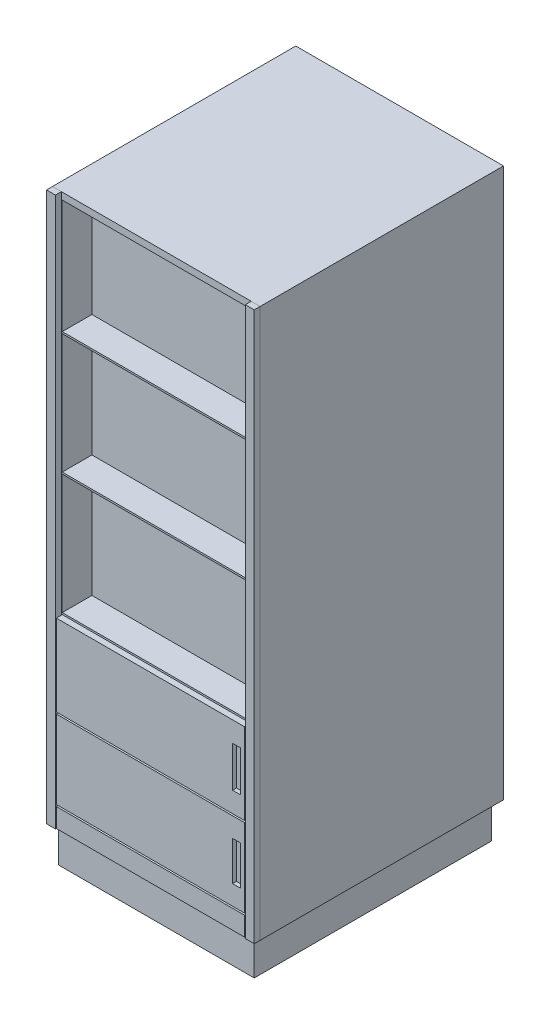
SolidWorks part; units mm, degrees
ref_plane "Front Plane" through (0, 0, 0) normal (0, 0, 1) x (1, 0, 0)
ref_plane "Top Plane" through (0, 0, 0) normal (0, 1, 0) x (1, 0, 0)
ref_plane "Right Plane" through (0, 0, 0) normal (1, 0, 0) x (0, 0, -1)
other "Configuration Table"
sketch "Sketch1" plane through (0, 0, 0) normal (0, 0, 1) x (1, 0, 0)
  line L1 (0, 120) -> (700, 120)
  line L2 (0, 120) -> (0, 1970)
  line L3 (0, 1970) -> (700, 1970)
  line L4 (700, 120) -> (700, 1970)
extrude "govde_kasa" add sketch "Sketch1" against normal blind 820 separate body
sketch "Sketch2" plane through (0, 0, 0) normal (0, 0, 1) x (1, 0, 0)
  line L1 (20, 0) -> (680, 0)
  line L2 (20, 0) -> (20, 120)
  line L3 (20, 120) -> (680, 120)
  line L4 (680, 0) -> (680, 120)
extrude "plint" add sketch "Sketch2" against normal blind 800 separate body
sketch "Sketch3" plane through (0, 0, 0) normal (0, 0, 1) x (1, 0, 0)
  line L1 (0, 120) -> (30, 120)
  line L2 (0, 120) -> (0, 1970)
  line L3 (0, 1970) -> (30, 1970)
  line L4 (30, 120) -> (30, 1970)
extrude "sove_sol" add sketch "Sketch3" along normal blind 20 separate body
sketch "Sketch4" plane through (0, 0, 0) normal (0, 0, 1) x (1, 0, 0)
  line L1 (670, 120) -> (700, 120)
  line L2 (670, 120) -> (670, 1970)
  line L3 (670, 1970) -> (700, 1970)
  line L4 (700, 120) -> (700, 1970)
extrude "sove_sag" add sketch "Sketch4" along normal blind 20 separate body
sketch "Sketch5" plane through (0, 0, 0) normal (0, 0, 1) x (1, 0, 0)
  line L1 (33, 1563) -> (667, 1563)
  line L2 (33, 1563) -> (33, 1947)
  line L3 (33, 1947) -> (667, 1947)
  line L4 (667, 1563) -> (667, 1947)
extrude "aciklik_kat1" cut sketch "Sketch5" against normal blind 100
sketch "Sketch6" plane through (0, 0, 0) normal (0, 0, 1) x (1, 0, 0)
  line L1 (33, 1153) -> (667, 1153)
  line L2 (33, 1153) -> (33, 1557)
  line L3 (33, 1557) -> (667, 1557)
  line L4 (667, 1153) -> (667, 1557)
extrude "aciklik_kat2" cut sketch "Sketch6" against normal blind 100
sketch "Sketch7" plane through (0, 0, 0) normal (0, 0, 1) x (1, 0, 0)
  line L1 (33, 743) -> (667, 743)
  line L2 (33, 743) -> (33, 1147)
  line L3 (33, 1147) -> (667, 1147)
  line L4 (667, 743) -> (667, 1147)
extrude "aciklik_kat3" cut sketch "Sketch7" against normal blind 100
sketch "Sketch8" plane through (0, 0, 0) normal (0, 0, 1) x (1, 0, 0)
  line L1 (33, 463) -> (667, 463)
  line L2 (33, 463) -> (33, 737)
  line L3 (33, 737) -> (667, 737)
  line L4 (667, 463) -> (667, 737)
extrude "klape_alt_1" add sketch "Sketch8" along normal blind 20 separate body
sketch "Sketch9" plane through (0, 0, 0) normal (0, 0, 1) x (1, 0, 0)
  line L1 (627, 531.5) -> (653, 531.5)
  line L2 (627, 531.5) -> (627, 668.5)
  line L3 (627, 668.5) -> (653, 668.5)
  line L4 (653, 531.5) -> (653, 668.5)
extrude "klape_alt_1_kulp" cut sketch "Sketch9" along normal blind 13 from offset 7
sketch "Sketch10" plane through (0, 0, 0) normal (0, 0, 1) x (1, 0, 0)
  line L1 (33, 193) -> (667, 193)
  line L2 (33, 193) -> (33, 457)
  line L3 (33, 457) -> (667, 457)
  line L4 (667, 193) -> (667, 457)
extrude "klape_alt_2" add sketch "Sketch10" along normal blind 20 separate body
sketch "Sketch11" plane through (0, 0, 0) normal (0, 0, 1) x (1, 0, 0)
  line L1 (627, 259) -> (653, 259)
  line L2 (627, 259) -> (627, 391)
  line L3 (627, 391) -> (653, 391)
  line L4 (653, 259) -> (653, 391)
extrude "klape_alt_2_kulp" cut sketch "Sketch11" along normal blind 13 from offset 7
sketch "Sketch12" plane through (0, 0, 0) normal (0, 0, 1) x (1, 0, 0)
  line L1 (33, 123) -> (667, 123)
  line L2 (33, 123) -> (33, 187)
  line L3 (33, 187) -> (667, 187)
  line L4 (667, 123) -> (667, 187)
extrude "panel_alt" add sketch "Sketch12" along normal blind 20 separate body
